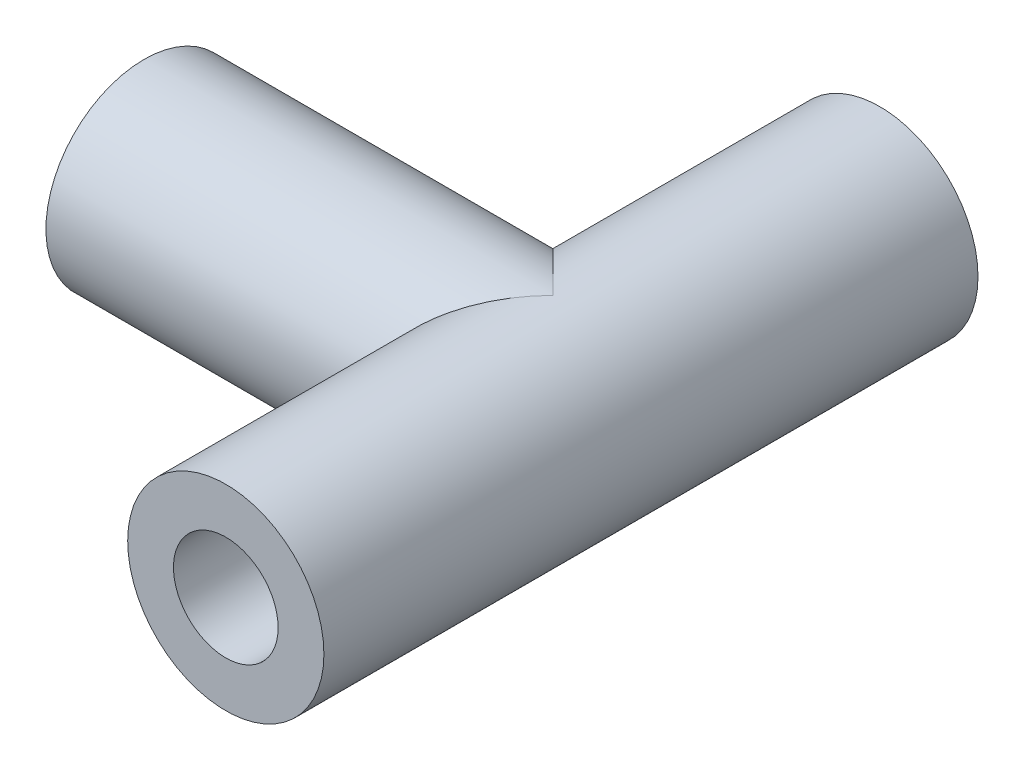
SolidWorks part; units mm, degrees
ref_plane "Front Plane" through (0, 0, 0) normal (0, 0, 1) x (1, 0, 0)
ref_plane "Top Plane" through (0, 0, 0) normal (0, 1, 0) x (1, 0, 0)
ref_plane "Right Plane" through (0, 0, 0) normal (1, 0, 0) x (0, 0, -1)
other "Configuration Table"
sketch "Sketch1" plane through (0, 0, 0) normal (1, 0, 0) x (0, 0, -1)
  circle A0 centre (0, 0) radius 6
  dimension "D1" = 12
extrude "Branch_Hub" add sketch "Sketch1" along normal blind 13 from offset 13
sketch "Sketch2" plane through (0, 0, 0) normal (0, 0, 1) x (1, 0, 0)
  circle A0 centre (0, 0) radius 6
  dimension "D1" = 12
extrude "Run_Back_Port" add sketch "Sketch2" along normal blind 12 from offset 20
sketch "Sketch3" plane through (0, 0, 0) normal (0, 0, 1) x (1, 0, 0)
  circle A0 centre (0, 0) radius 3.2
  dimension "D1" = 6.4
extrude "Run_Back_Socket" cut sketch "Sketch3" along normal blind 10 from offset 20
sketch "Sketch4" plane through (0, 0, 0) normal (0, 0, 1) x (1, 0, 0)
  circle A0 centre (0, 0) radius 6
  dimension "D1" = 12
extrude "Run_Front_Port" add sketch "Sketch4" along normal blind 12 from offset 8
sketch "Sketch5" plane through (0, 0, 0) normal (0, 0, 1) x (1, 0, 0)
  circle A0 centre (0, 0) radius 3.2
  dimension "D1" = 6.4
extrude "Run_Front_Socket" cut sketch "Sketch5" against normal blind 10 from offset 20
sketch "Sketch6" plane through (0, 0, 0) normal (0, 0, 1) x (1, 0, 0)
  circle A0 centre (0, 0) radius 6
  dimension "D1" = 12
extrude "Run_Hub" add sketch "Sketch6" along normal blind 16 from offset 8
sketch "Sketch7" plane through (0, 0, 0) normal (1, 0, 0) x (0, 0, -1)
  circle A0 centre (0, 0) radius 6
  dimension "D1" = 12
extrude "Branch_Port" add sketch "Sketch7" along normal blind 12 from offset 25
sketch "Sketch8" plane through (0, 0, 0) normal (1, 0, 0) x (0, 0, -1)
  circle A0 centre (0, 0) radius 3.2
  dimension "D1" = 6.4
extrude "Branch_Socket" cut sketch "Sketch8" along normal blind 10 from offset 25
equation "\"Jar_OD\"= 90  'ASSUMED - Part G fallback - jar outer diameter"
equation "\"Jar_H\"= 120  'ASSUMED - Part G fallback - jar height"
equation "\"Pump_L\"= 45  'ASSUMED - Part G fallback"
equation "\"Pump_W\"= 24  'ASSUMED - Part G fallback"
equation "\"Pump_H\"= 33  'ASSUMED - Part G fallback"
equation "\"Pump_Outlet_OD\"= 7.5  'ASSUMED - Part G fallback"
equation "\"Tube_OD\"= 8  'ASSUMED - Part G fallback"
equation "\"Tube_ID\"= 6  'ASSUMED - Part G fallback"
equation "\"TDS_Body_Dia\"= 12  'ASSUMED - Part G fallback"
equation "\"TDS_Wet_Len\"= 45  'ASSUMED - Part G fallback - length in water"
equation "\"DS_Tube_Dia\"= 6  'ASSUMED - Part G fallback"
equation "\"DS_Tube_Len\"= 50  'ASSUMED - Part G fallback"
equation "\"ORP_Body_Dia\"= 12  'ASSUMED - Part G fallback"
equation "\"ORP_Body_Len\"= 150  'ASSUMED - Part G fallback"
equation "\"ORP_Cap_Dia\"= 16  'ASSUMED - Part G fallback"
equation "\"Turb_W\"= 33  'ASSUMED - Part G fallback - head width"
equation "\"Turb_D\"= 28  'ASSUMED - Part G fallback - head depth"
equation "\"Turb_H\"= 30  'ASSUMED - Part G fallback - head height"
equation "\"Turb_Slot_W\"= 10  'ASSUMED - Part G fallback - slot width"
equation "\"Flow_L\"= 62  'ASSUMED - Part G fallback YF-S201"
equation "\"Flow_W\"= 36  'ASSUMED - Part G fallback"
equation "\"Flow_H\"= 35  'ASSUMED - Part G fallback"
equation "\"Thread_G12_OD\"= 20.955  'ASSUMED - Part G fallback thread G1/2 (major diameter)"
equation "\"Valve_L\"= 75  'ASSUMED - Part G fallback"
equation "\"Valve_W\"= 45  'ASSUMED - Part G fallback"
equation "\"Valve_H\"= 60  'ASSUMED - Part G fallback"
equation "\"Tee_L\"= 40  'ASSUMED - Part G fallback - overall length"
equation "\"Tee_Branch_L\"= 25  'ASSUMED - Part G fallback"
equation "\"Tee_OD\"= 12  'ASSUMED - Part G fallback"
equation "\"LED_Board_L\"= 20  'ASSUMED - Part G fallback"
equation "\"LED_Board_W\"= 20  'ASSUMED - Part G fallback - LED at centre"
equation "\"GUVA_L\"= 20  'ASSUMED - Part G fallback"
equation "\"GUVA_W\"= 12  'ASSUMED - Part G fallback - sensor at centre"
equation "\"Reed_L\"= 27  'ASSUMED - Part G fallback MC-38 half"
equation "\"Reed_W\"= 14  'ASSUMED - Part G fallback"
equation "\"Reed_H\"= 8  'ASSUMED - Part G fallback"
equation "\"ESP_L\"= 51  'ASSUMED - Part G fallback"
equation "\"ESP_W\"= 28  'ASSUMED - Part G fallback"
equation "\"TFT_L\"= 58  'ASSUMED - Part G fallback - board"
equation "\"TFT_W\"= 35  'ASSUMED - Part G fallback - board"
equation "\"TFT_Win_L\"= 35  'ASSUMED - Part G fallback - visible window"
equation "\"TFT_Win_W\"= 28  'ASSUMED - Part G fallback - visible window"
equation "\"Relay_L\"= 50  'ASSUMED - Part G fallback"
equation "\"Relay_W\"= 26  'ASSUMED - Part G fallback"
equation "\"Relay_H\"= 19  'ASSUMED - Part G fallback"
equation "\"Mosfet_L\"= 34  'ASSUMED - Part G fallback"
equation "\"Mosfet_W\"= 17  'ASSUMED - Part G fallback"
equation "\"Mosfet_H\"= 12  'ASSUMED - Part G fallback"
equation "\"TDS_Board_L\"= 42  'ASSUMED - Part G fallback"
equation "\"TDS_Board_W\"= 32  'ASSUMED - Part G fallback"
equation "\"Turb_Board_L\"= 38  'ASSUMED - Part G fallback"
equation "\"Turb_Board_W\"= 28  'ASSUMED - Part G fallback"
equation "\"BNC_Thread_Dia\"= 9.5  'ASSUMED - Part G fallback"
equation "\"Plate_L\"= 420  'ASSUMED - Part G fallback"
equation "\"Plate_W\"= 297  'ASSUMED - Part G fallback"
equation "\"Plate_T\"= 6  'ASSUMED - Part G fallback"
equation "\"Booster_L\"= 150  'ASSUMED - Part G fallback - booster pump"
equation "\"Booster_W\"= 95  'ASSUMED - Part G fallback"
equation "\"Booster_H\"= 100  'ASSUMED - Part G fallback"
equation "\"PTube_OD\"= 6.35  'ASSUMED - Part G fallback - product tube 1/4 inch"
equation "\"Qz_Out\"= 12  'ASSUMED - Part G fallback - quartz channel outside square"
equation "\"Qz_Path\"= 10  'ASSUMED - Part G fallback - quartz channel inside light path"
equation "\"Qz_L\"= 40  'ASSUMED - Part G fallback - quartz channel length"
equation "\"LED860_Dia\"= 5  'ASSUMED - Part G fallback - 860 nm LED"
equation "\"BPW_L\"= 5.4  'ASSUMED - Part G fallback - BPW34"
equation "\"BPW_W\"= 4.3  'ASSUMED - Part G fallback - BPW34"
equation "\"Cart_Dia\"= 50  'ASSUMED - Part G fallback - sediment and pre-carbon cartridges"
equation "\"Cart_L\"= 255  'ASSUMED - Part G fallback"
equation "\"UF_Dia\"= 50  'ASSUMED - Part G fallback - UF cartridge"
equation "\"UF_L\"= 260  'ASSUMED - Part G fallback"
equation "\"RO_Dia\"= 62  'ASSUMED - Part G fallback - RO membrane housing"
equation "\"RO_L\"= 300  'ASSUMED - Part G fallback"
equation "\"UVC_Dia\"= 40  'ASSUMED - Part G fallback - UV-C chamber"
equation "\"UVC_L\"= 300  'ASSUMED - Part G fallback"
equation "\"Tank_W\"= 260  'ASSUMED - Part G fallback - storage tank"
equation "\"Tank_D\"= 160  'ASSUMED - Part G fallback"
equation "\"Tank_H\"= 300  'ASSUMED - Part G fallback"
equation "\"Cab_W\"= 400  'ASSUMED - Part G fallback - purifier cabinet"
equation "\"Cab_D\"= 270  'ASSUMED - Part G fallback"
equation "\"Cab_H\"= 560  'ASSUMED - Part G fallback"
equation "\"ORP_Board_L\"= 40  'ASSUMED - Part G fallback - ORP buffer board"
equation "\"ORP_Board_W\"= 30  'ASSUMED - Part G fallback"
equation "\"Opt_Board_L\"= 50  'ASSUMED - Part G fallback - optical front-end board"
equation "\"Opt_Board_W\"= 40  'ASSUMED - Part G fallback"
equation "\"Buck_L\"= 43  'ASSUMED - Part G fallback - 12 V to 5 V buck module"
equation "\"Buck_W\"= 21  'ASSUMED - Part G fallback"
equation "\"Buck_H\"= 14  'ASSUMED - Part G fallback"
equation "\"BB_L\"= 165  'ASSUMED - Part G fallback - breadboard (As_Built_R3 only)"
equation "\"BB_W\"= 55  'ASSUMED - Part G fallback"
equation "\"BB_H\"= 10  'ASSUMED - Part G fallback"
equation "\"Cuv_W\"= 12.5  'ASSUMED - old R3 cuvette (station suppressed in SS4)"
equation "\"Cuv_D\"= 12.5  'ASSUMED - old R3 cuvette (station suppressed in SS4)"
equation "\"Cuv_H\"= 45  'ASSUMED - old R3 cuvette (station suppressed in SS4)"
equation "\"Probe_Clr\"= 0.3  'DESIGN VALUE - Part C rule 3 - printed probe hole = diameter + 0.3"
equation "\"Label_H\"= 0.6  'DESIGN VALUE - Part D - raised label height"
